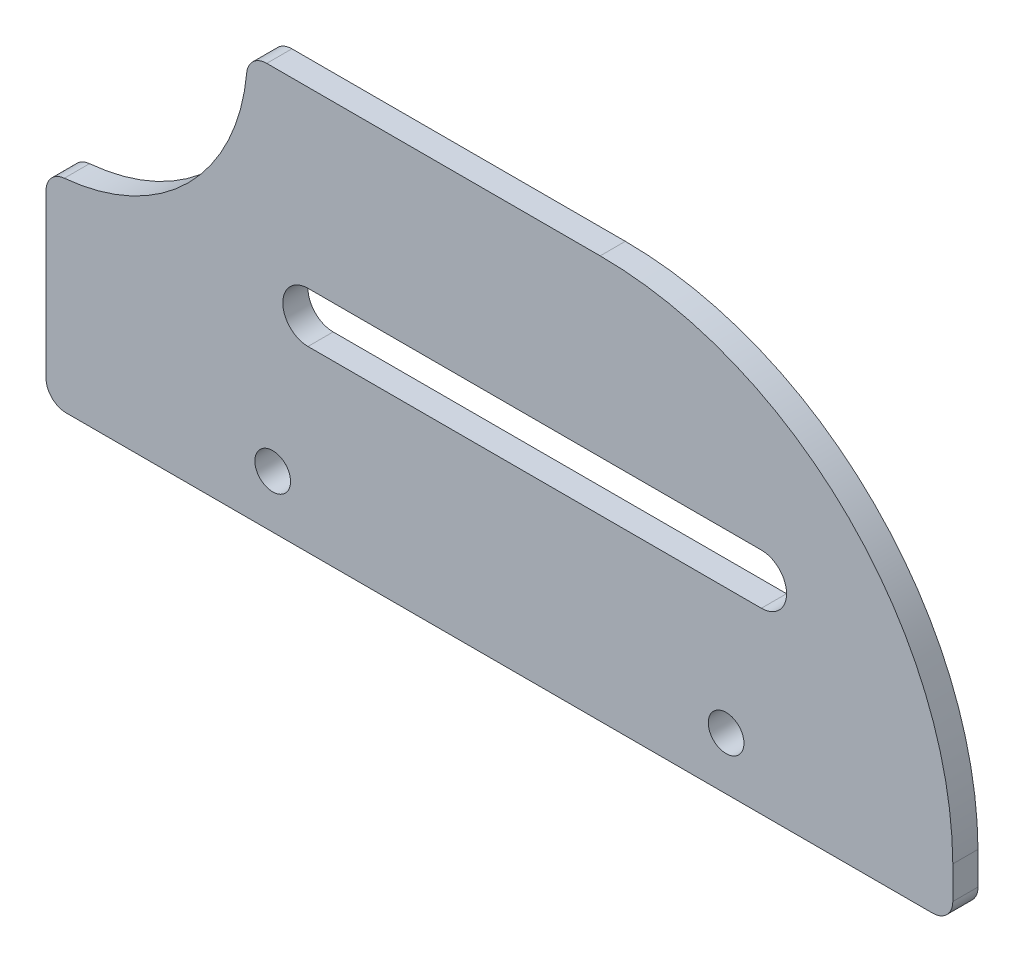
SolidWorks part; units mm, degrees
material "AISI 4130 Steel, annealed at 865C"
ref_plane "X-Y Datum" through (0, 0, 0) normal (0, 0, 1) x (1, 0, 0)
ref_plane "X-Z Datum" through (0, 0, 0) normal (0, 1, 0) x (1, 0, 0)
ref_plane "Y-Z Datum" through (0, 0, 0) normal (1, 0, 0) x (0, 0, -1)
sketch "Sketch1" plane through (0, 0, 0) normal (0, 0, 1) x (1, 0, 0)
  line L1 (0, 0) -> (114.3, 0)
  line L2 (0, 0) -> (0, 50.8)
  line L3 (0, 50.8) -> (114.3, 50.8)
  line L4 (114.3, 0) -> (114.3, 50.8)
  arc A1 (25.4, 50.8) -> (0, 25.4) centre (0, 50.8) cw
  dimension "D1" = 50.8
  dimension "D2" = 114.3
extrude "Boss-Extrude1" add sketch "Sketch1" along normal blind 3.175 contours L3 A1 L2 L1 L4
sketch "Sketch2" plane through (0, 0, 3.175) normal (0, 0, 1) x (1, 0, 0)
  line L0 (57.15, 0) -> (57.15, 6.65) construction
  line L1 (0, 0) -> (114.3, 0) construction
  line L2 (57.15, 6.65) -> (114.3, 6.65) construction
  line L3 (114.3, 0) -> (114.3, 50.8) construction
  line L4 (57.15, 6.65) -> (0, 6.65) construction
  line L5 (0, 0) -> (0, 25.4) construction
  line L6 (25.4, 50.8) -> (114.3, 50.8) construction
  line L7 (114.3, 50.8) -> (114.3, 0) construction
  line L8 (25.4, 50.8) -> (69.85, 50.8)
  line L9 (90.17, 25.6685) -> (33.02, 25.6685) construction
  line L10 (90.17, 22.4935) -> (33.02, 22.4935)
  line L11 (90.17, 28.8435) -> (33.02, 28.8435)
  circle A0 centre (85.725, 6.65) radius 2.25
  circle A1 centre (28.575, 6.65) radius 2.25
  arc A2 (69.85, 50.8) -> (114.3, 6.65) centre (69.85, 6.349) cw
  arc A3 (90.17, 22.4935) -> (90.17, 28.8435) centre (90.17, 25.6685) ccw
  arc A4 (33.02, 28.8435) -> (33.02, 22.4935) centre (33.02, 25.6685) ccw
  point P24 (61.595, 25.6685)
  line M3 (114.3, 50.8) -> (25.4, 50.8)
  line M7 (114.3, 0) -> (114.3, 50.8)
  dimension "D2" = 4.5
  dimension "D3" = 4.5
  dimension "D4" = 57.15
  dimension "D1" = 6.65
  dimension "D5" = 6.35
  dimension "D6" = 24.13
extrude "Cut-Extrude1" cut sketch "Sketch2" against normal through all contours A2 M3 M7 | A0 | L11 A4 L10 A3 | A1
fillet "Fillet1" radius 2.54 4 edges at (25.4, 50.8, 1.5875) (0, 25.4, 1.5875) (0, 0, 1.5875) (114.3, 0, 1.5875)
sketch "Sketch3" plane through (0, 0, 3.175) normal (0, 0, 1) x (1, 0, 0)
  arc A0 (2.3091, 25.5052) -> (25.2948, 48.4909) centre (0, 50.8) ccw construction
  arc A1 (2.3091, 25.5052) -> (25.2948, 48.4909) centre (0, 50.8) ccw
  point P3 (0, 0)
  point P5 (17.9605, 32.8395)
